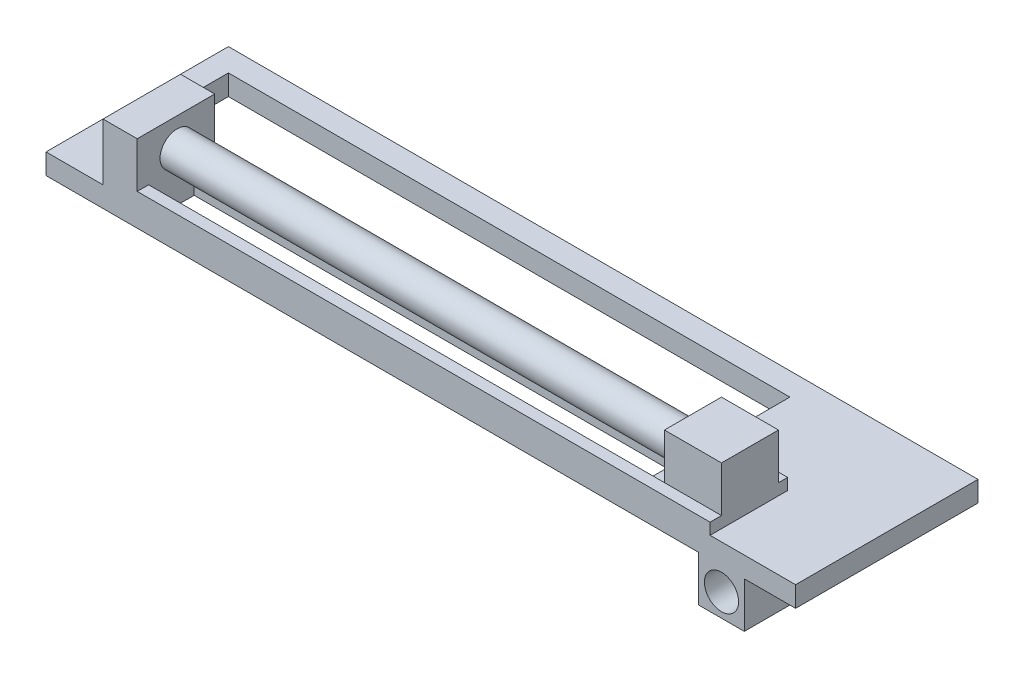
SolidWorks part; units mm, degrees
ref_plane "前视基准面" through (0, 0, 0) normal (0, 0, 1) x (1, 0, 0)
ref_plane "上视基准面" through (0, 0, 0) normal (0, 1, 0) x (1, 0, 0)
ref_plane "右视基准面" through (0, 0, 0) normal (1, 0, 0) x (0, 0, -1)
sketch "草图1" plane through (0, 0, 0) normal (0, 0, 1) x (1, 0, 0)
  line L1 (0, 0) -> (131.5, 0)
  line L2 (0, 0) -> (0, 3.6)
  line L3 (0, 3.6) -> (131.5, 3.6)
  line L4 (131.5, 0) -> (131.5, 3.6)
  dimension "D1" = 131.5
  dimension "D2" = 3.6
extrude "凸台-拉伸1" add sketch "草图1" against normal blind 4 contours L2 L1 L4 L3
sketch "草图2" plane through (0, 0, -4) normal (0, 0, -1) x (-1, 0, 0)
  line L0 (0, 0) -> (-131.5, 0) construction
  line L1 (-131.5, 3.6) -> (-127.5, 3.6)
  line L2 (-131.5, 3.6) -> (-131.5, 0)
  line L3 (-131.5, 0) -> (-127.5, 0)
  line L4 (-127.5, 3.6) -> (-127.5, 0)
  line L5 (-65.75, 3.6) -> (-65.75, 0) construction
  line L7 (0, 0) -> (0, 3.6) construction
  line L8 (-4, 3.6) -> (-4, 0)
  line L9 (0, 0) -> (-4, 0)
  line L10 (0, 3.6) -> (0, 0)
  line L11 (0, 3.6) -> (-4, 3.6)
  dimension "D1" = 65.75
  dimension "D2" = 4
extrude "凸台-拉伸2" add sketch "草图2" along normal blind 28 contours L8 L9 L10 L11
sketch "草图3" plane through (0, 0, -4) normal (0, 0, -1) x (-1, 0, 0)
  line L0 (-4, 0) -> (-131.5, 0) construction
  line L1 (-131.5, 3.6) -> (-127.5, 3.6)
  line L2 (-131.5, 3.6) -> (-131.5, 0)
  line L3 (-131.5, 0) -> (-127.5, 0)
  line L4 (-127.5, 3.6) -> (-127.5, 0)
  dimension "D1" = 4
extrude "凸台-拉伸3" add sketch "草图3" along normal blind 28 contours L2 L1 L4 L3
sketch "草图4" plane through (4, 0, 0) normal (1, 0, 0) x (0, 0, -1)
  line L0 (32, 0) -> (4, 0) construction
  line L1 (32, 3.6) -> (28, 3.6)
  line L2 (32, 3.6) -> (32, 0)
  line L3 (32, 0) -> (28, 0)
  line L4 (28, 3.6) -> (28, 0)
  dimension "D1" = 4
extrude "凸台-拉伸4" add sketch "草图4" along normal up to surface (123.5 mm away) contours L2 L1 L4 L3 up to face at (127.5, 1.8, -18)
sketch "草图5" plane through (0, 0, 0) normal (0, -1, 0) x (1, 0, 0)
  line L0 (0, 0) -> (131.5, 0) construction
  line L1 (114.5, 0) -> (122.5, 0)
  line L2 (114.5, 0) -> (114.5, -32)
  line L3 (114.5, -32) -> (122.5, -32)
  line L4 (122.5, 0) -> (122.5, -32)
  line L5 (0, -32) -> (131.5, -32) construction
  line L6 (127.5, -28) -> (127.5, -4) construction
  dimension "D1" = 8
  dimension "D2" = 5
extrude "凸台-拉伸5" add sketch "草图5" along normal blind 8 contours L2 L1 L4 L3
sketch "草图6" plane through (0, 0, 0) normal (0, 0, 1) x (1, 0, 0)
  line L0 (118.5, -8) -> (118.5, 3.6) construction
  line L1 (114.5, -8) -> (122.5, -8) construction
  line L2 (114.5, -4) -> (122.5, -4) construction
  line L3 (114.5, -8) -> (114.5, 0) construction
  line L4 (122.5, -8) -> (122.5, 0) construction
  line L5 (0, 3.6) -> (131.5, 3.6) construction
  circle A0 centre (118.5, -4) radius 3
  dimension "D1" = 6
extrude "切除-拉伸1" cut sketch "草图6" against normal up to next
sketch "草图7" plane through (0, 0, -4) normal (0, 0, -1) x (-1, 0, 0)
  line L0 (-4, 0) -> (-114.5, 0) construction
  line L1 (-127.5, 3.6) -> (-102.5, 3.6)
  line L2 (-127.5, 3.6) -> (-127.5, 0)
  line L3 (-127.5, 0) -> (-102.5, 0)
  line L4 (-102.5, 3.6) -> (-102.5, 0)
  dimension "D1" = 25
extrude "凸台-拉伸6" add sketch "草图7" along normal up to next contours L2 L1 L4 L3
sketch "草图8" plane through (102.5, 0, 0) normal (-1, 0, 0) x (0, 0, 1)
  line L0 (-28, 3.6) -> (-4, 3.6) construction
  line L1 (-13.6, 3.6) -> (-10, 3.6)
  line L2 (-13.6, 3.6) -> (-13.6, 0)
  line L3 (-13.6, 0) -> (-10, 0)
  line L4 (-10, 3.6) -> (-10, 0)
  line L5 (-28, 0) -> (-4, 0) construction
  line L6 (-4, 3.6) -> (-4, 0) construction
  dimension "D1" = 3.6
  dimension "D2" = 6
extrude "凸台-拉伸7" add sketch "草图8" along normal up to next contours L2 L1 L4 L3
sketch "草图9" plane through (0, 3.6, 0) normal (0, 1, 0) x (1, 0, 0)
  line L0 (0, 0) -> (131.5, 0) construction
  line L1 (111.461, 10) -> (121.461, 10)
  line L2 (111.461, 10) -> (111.461, 0)
  line L3 (111.461, 0) -> (121.461, 0)
  line L4 (121.461, 10) -> (121.461, 0)
  dimension "D1" = 10
  dimension "D2" = 10
sketch "草图13" plane through (0, 3.6, 0) normal (0, 1, 0) x (1, 0, 0)
  line L0 (0, 0) -> (131.5, 0) construction
  line L1 (106.5, 12) -> (116.5, 12)
  line L2 (106.5, 12) -> (106.5, 2)
  line L3 (106.5, 2) -> (116.5, 2)
  line L4 (116.5, 12) -> (116.5, 2)
  line L5 (102.5, 10) -> (102.5, 4) construction
  dimension "D1" = 10
  dimension "D2" = 10
  dimension "D3" = 2
  dimension "D4" = 4
extrude "凸台-拉伸8" add sketch "草图13" along normal blind 10 contours L2 L1 L4 L3
sketch "草图14" plane through (0, 0, -10) normal (0, 0, 1) x (1, 0, 0)
  line L0 (4, 3.6) -> (102.5, 3.6) construction
  line L1 (4, 0) -> (16, 0)
  line L2 (4, 0) -> (4, 3.6)
  line L3 (4, 3.6) -> (16, 3.6)
  line L4 (16, 0) -> (16, 3.6)
  dimension "D1" = 12
extrude "凸台-拉伸9" add sketch "草图14" along normal up to next contours L2 L1 L4 L3
sketch "草图15" plane through (0, 3.6, 0) normal (0, 1, 0) x (1, 0, 0)
  line L0 (4, 13.6) -> (102.5, 13.6) construction
  line L1 (16, 13.6) -> (10, 13.6)
  line L2 (16, 13.6) -> (16, 0)
  line L3 (16, 0) -> (10, 0)
  line L4 (10, 13.6) -> (10, 0)
  line L5 (0, 0) -> (131.5, 0) construction
  line L6 (16, 4) -> (16, 10) construction
  dimension "D1" = 6
extrude "凸台-拉伸10" add sketch "草图15" along normal blind 10 contours L2 L1 L4 L3
sketch "草图16" plane through (106.5, 0, 0) normal (-1, 0, 0) x (0, 0, 1)
  line L0 (-7, 3.6) -> (-7, 13.6) construction
  line L1 (-12, 3.6) -> (-2, 3.6) construction
  line L2 (-12, 13.6) -> (-2, 13.6) construction
  line L3 (-12, 8.6) -> (-2, 8.6) construction
  line L4 (-12, 13.6) -> (-12, 3.6) construction
  line L5 (-2, 13.6) -> (-2, 3.6) construction
  circle A0 centre (-7, 8.6) radius 3
  dimension "D1" = 6
extrude "凸台-拉伸11" add sketch "草图16" along normal up to next contours A0
sketch "草图17" plane through (0, 3.6, 0) normal (0, 1, 0) x (1, 0, 0)
  line L9 (16, 0) -> (116.5, 0)
  line L10 (16, 0) -> (16, 2)
  line L11 (16, 2) -> (116.5, 2)
  line L12 (116.5, 0) -> (116.5, 2)
extrude "凸台-拉伸12" add sketch "草图17" along normal blind 2 contours L10 L9 L12 L11
sketch "草图18" plane through (0, 3.6, 0) normal (0, 1, 0) x (1, 0, 0)
  line L1 (16, 13.6) -> (116.5, 13.6)
  line L2 (16, 13.6) -> (16, 12)
  line L3 (16, 12) -> (116.5, 12)
  line L4 (116.5, 13.6) -> (116.5, 12)
extrude "凸台-拉伸13" add sketch "草图18" along normal blind 2
